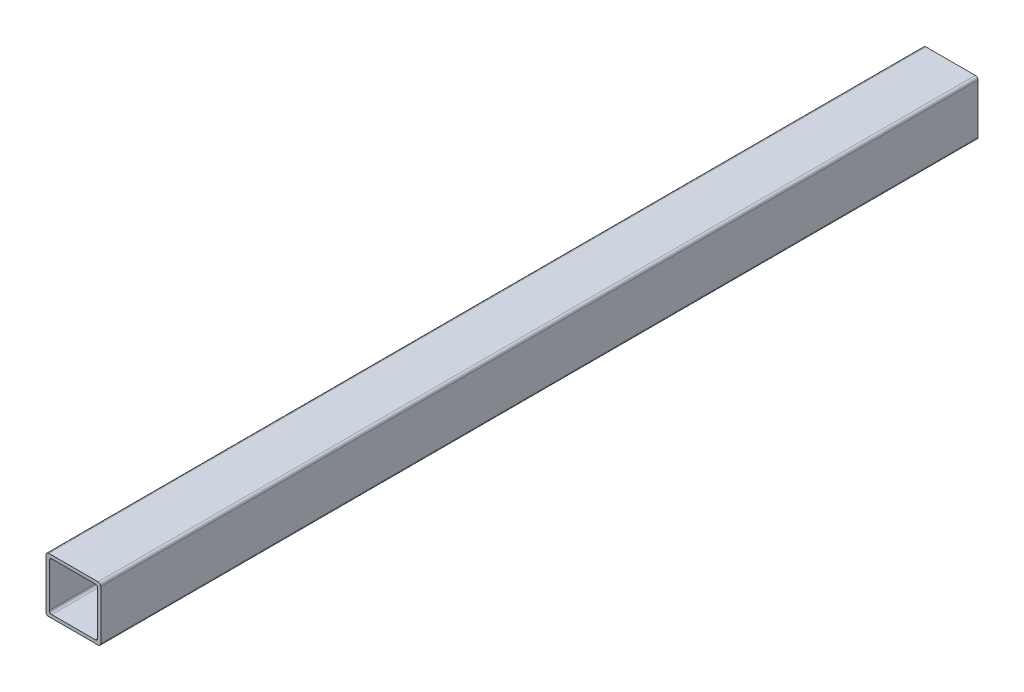
SolidWorks part; units mm, degrees
material "AISI 1020"
ref_plane "Plan de face" through (0, 0, 0) normal (0, 0, 1) x (1, 0, 0)
ref_plane "Plan de dessus" through (0, 0, 0) normal (0, 1, 0) x (1, 0, 0)
ref_plane "Plan de droite" through (0, 0, 0) normal (1, 0, 0) x (0, 0, -1)
ref_plane "Plan1" through (0, 0, 406.4) normal (0, 0, 1) x (1, 0, 0)
sketch "Esquisse1" plane through (0, 0, 406.4) normal (0, 0, 1) x (1, 0, 0)
  line L0 (25.4, -22.86) -> (25.4, 22.86)
  line L1 (22.86, 25.4) -> (-22.86, 25.4)
  line L2 (-25.4, 22.86) -> (-25.4, -22.86)
  line L3 (-22.86, -25.4) -> (22.86, -25.4)
  line L4 (-20.1168, 22.352) -> (20.1168, 22.352)
  line L5 (22.352, 20.1168) -> (22.352, -20.1168)
  line L6 (20.1168, -22.352) -> (-20.1168, -22.352)
  line L7 (-22.352, -20.1168) -> (-22.352, 20.1168)
  arc A0 (22.86, -25.4) -> (25.4, -22.86) centre (22.86, -22.86) ccw
  arc A1 (25.4, 22.86) -> (22.86, 25.4) centre (22.86, 22.86) ccw
  arc A2 (-22.86, 25.4) -> (-25.4, 22.86) centre (-22.86, 22.86) ccw
  arc A3 (-25.4, -22.86) -> (-22.86, -25.4) centre (-22.86, -22.86) ccw
  arc A4 (20.1168, 22.352) -> (22.352, 20.1168) centre (20.1168, 20.1168) cw
  arc A5 (22.352, -20.1168) -> (20.1168, -22.352) centre (20.1168, -20.1168) cw
  arc A6 (-20.1168, -22.352) -> (-22.352, -20.1168) centre (-20.1168, -20.1168) cw
  arc A7 (-22.352, 20.1168) -> (-20.1168, 22.352) centre (-20.1168, 20.1168) cw
extrude "Boss.-Extru.1" add sketch "Esquisse1" against normal blind 812.8
